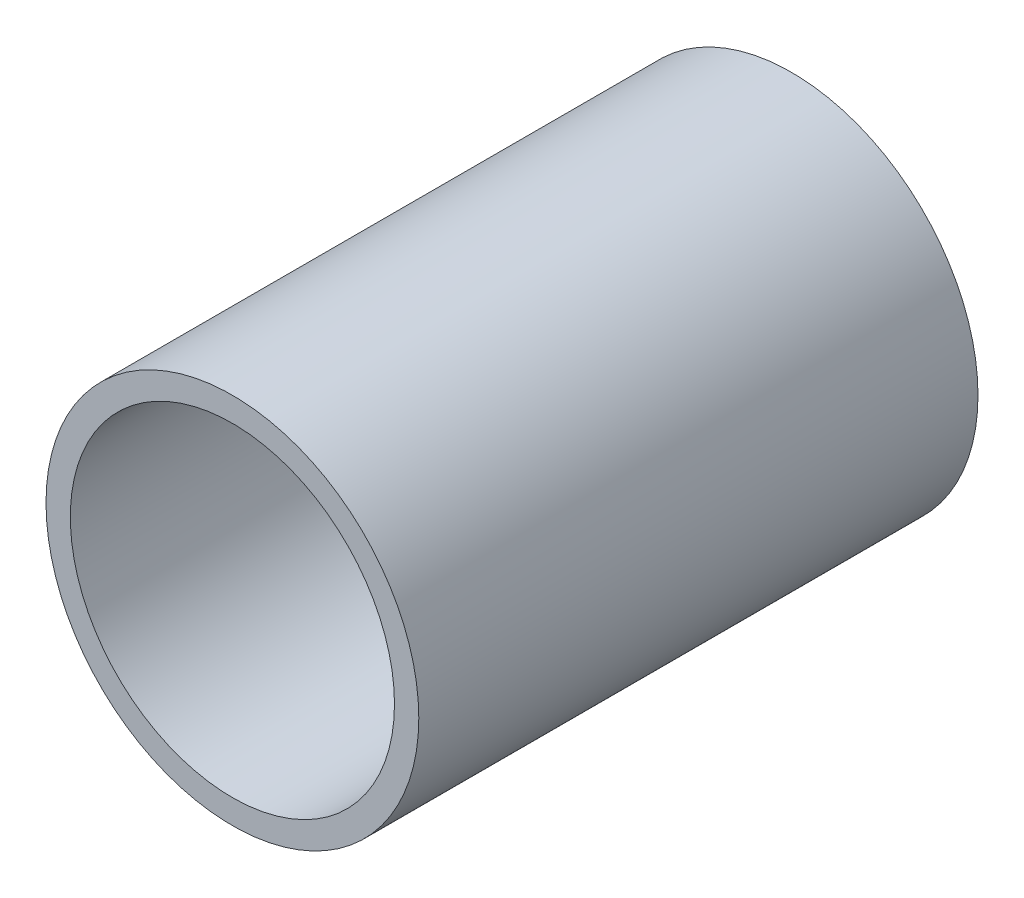
SolidWorks part; units mm, degrees
ref_plane "Front Plane" through (0, 0, 0) normal (0, 0, 1) x (1, 0, 0)
ref_plane "Top Plane" through (0, 0, 0) normal (0, 1, 0) x (1, 0, 0)
ref_plane "Right Plane" through (0, 0, 0) normal (1, 0, 0) x (0, 0, -1)
sketch "Sketch1" plane through (0, 0, 0) normal (0, 0, 1) x (1, 0, 0)
  line L0 (0, 0) -> (20, 0) construction
  line L1 (20, 0) -> (23, 0) construction
  circle A0 centre (0, 0) radius 23
  circle A1 centre (0, 0) radius 20
  dimension "D1" = 46
  dimension "D2" = 3
extrude "Boss-Extrude1" add sketch "Sketch1" along normal blind 69
